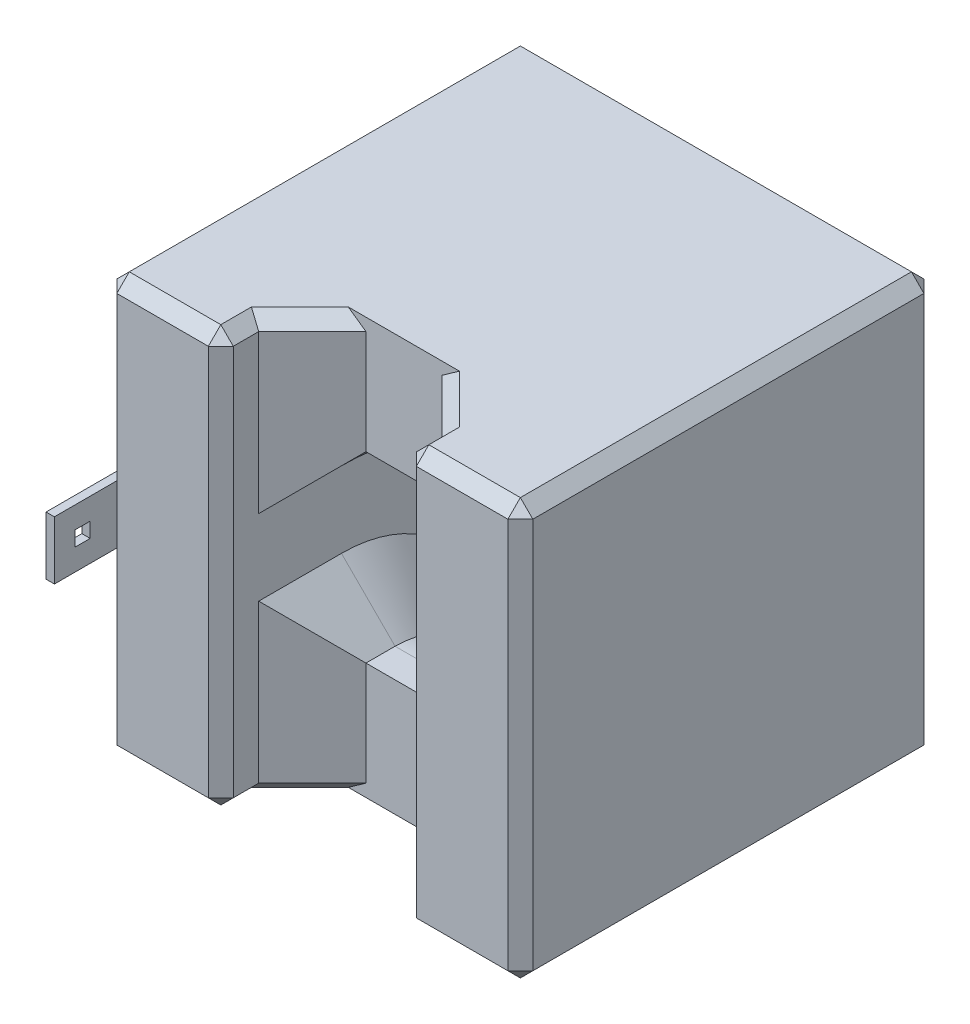
SolidWorks part; units mm, degrees
ref_plane "Front" through (0, 0, 0) normal (0, 0, 1) x (1, 0, 0)
ref_plane "Top" through (0, 0, 0) normal (0, 1, 0) x (1, 0, 0)
ref_plane "Right" through (0, 0, 0) normal (1, 0, 0) x (0, 0, -1)
sketch "Sketch1" plane through (0, 0, 0) normal (0, 0, 1) x (1, 0, 0)
  line L1 (0, 0) -> (50, 0)
  line L2 (0, 0) -> (0, 50)
  line L3 (0, 50) -> (50, 50)
  line L4 (50, 0) -> (50, 50)
  dimension "D1" = 50
extrude "Boss-Extrude1" add sketch "Sketch1" along normal blind 50
sketch "Sketch2" plane through (0, 0, 0) normal (0, -1, 0) x (1, 0, 0)
  line L0 (0, 50) -> (50, 50) construction
  line L1 (36, 45.4437) -> (36, 54.5563)
  line L2 (36, 54.5563) -> (29.5563, 61)
  line L3 (29.5563, 61) -> (20.4437, 61)
  line L4 (20.4437, 61) -> (14, 54.5563)
  line L5 (14, 54.5563) -> (14, 45.4437)
  line L6 (14, 45.4437) -> (20.4437, 39)
  line L7 (20.4437, 39) -> (29.5563, 39)
  line L8 (29.5563, 39) -> (36, 45.4437)
  circle A0 centre (25, 50) radius 11 construction
  dimension "D1" = 22
extrude "Cut-Extrude1" cut sketch "Sketch2" against normal through all
sketch "Sketch3" plane through (0, 0, 0) normal (0, -1, 0) x (1, 0, 0)
  line L0 (20.4437, 39) -> (29.5563, 39) construction
  line L1 (29.5563, 24.5) -> (20.4437, 24.5)
  line L2 (20.4437, 24.5) -> (14, 18.0563)
  line L3 (14, 18.0563) -> (14, 8.9437)
  line L4 (14, 8.9437) -> (20.4437, 2.5)
  line L5 (20.4437, 2.5) -> (29.5563, 2.5)
  line L6 (29.5563, 2.5) -> (36, 8.9437)
  line L7 (36, 8.9437) -> (36, 18.0563)
  line L8 (36, 18.0563) -> (29.5563, 24.5)
  line L9 (36, 45.4437) -> (36, 50) construction
  line L10 (50, 25) -> (25, 25) construction
  line L11 (50, 50) -> (50, 0) construction
  line L12 (25, 25) -> (25, 13.5) construction
  line L13 (25, 13.5) -> (25, 0) construction
  line L14 (0, 0) -> (50, 0) construction
  circle A0 centre (25, 13.5) radius 11 construction
  dimension "D1" = 2.5
ref_plane "Plane1" through (25, 0, 0) normal (1, 0, 0) x (0, 0, -1)
sketch "Sketch4" plane through (25, 0, 0) normal (1, 0, 0) x (0, 0, -1)
  line L0 (-13.5, 0) -> (-13.5, 3)
  line L1 (-35.5, 25) -> (-50, 25)
  line L2 (-50, 0) -> (-50, 50) construction
  arc A0 (-13.5, 3) -> (-35.5, 25) centre (-35.5, 3) ccw
  dimension "D1" = 22
sweep "Cut-Sweep1" cut profiles "Sketch3" path "Sketch4"
chamfer "Chamfer1" distance 1.5 angle 45 24 edges at (32.7782, 50, 42.2218) (36, 50, 47.7218) (0, 50, 25) (0, 25, 0) (25, 50, 0) (50, 25, 0) (43, 0, 50) (32.7782, 0, 42.2218) (36, 0, 47.7218) (36, 25, 50) (50, 50, 25) (43, 50, 50) (50, 25, 50) (50, 0, 25) (25, 0, 0) (7, 50, 50) (17.2218, 50, 42.2218) (14, 50, 47.7218) (0, 0, 25) (0, 25, 50) (7, 0, 50) (14, 25, 50) (14, 0, 47.7218) (17.2218, 0, 42.2218)
sketch "Sketch5" plane through (0, 0, 50) normal (0, 0, 1) x (1, 0, 0)
  line L0 (0, 1.5) -> (0, 48.5) construction
  line L1 (0, 28.5) -> (1, 28.5)
  line L2 (0, 28.5) -> (0, 21.5)
  line L3 (0, 21.5) -> (1, 21.5)
  line L4 (1, 28.5) -> (1, 21.5)
  point P6 (0, 25)
  dimension "D1" = 1
  dimension "D2" = 7
extrude "Boss-Extrude2" add sketch "Sketch5" along normal blind 7 and the other way blind 10
sketch "Sketch6" plane through (1, 0, 0) normal (1, 0, 0) x (0, 0, -1)
  line L0 (-54.5, 25) -> (-57, 25) construction
  line L1 (-54.5, 24.1) -> (-52.7, 24.1)
  line L2 (-54.5, 24.1) -> (-54.5, 25.9)
  line L3 (-54.5, 25.9) -> (-52.7, 25.9)
  line L4 (-52.7, 24.1) -> (-52.7, 25.9)
  line L5 (-57, 21.5) -> (-57, 28.5) construction
  dimension "D1" = 2.5
  dimension "D2" = 1.8
extrude "Cut-Extrude2" cut sketch "Sketch6" against normal blind 7
